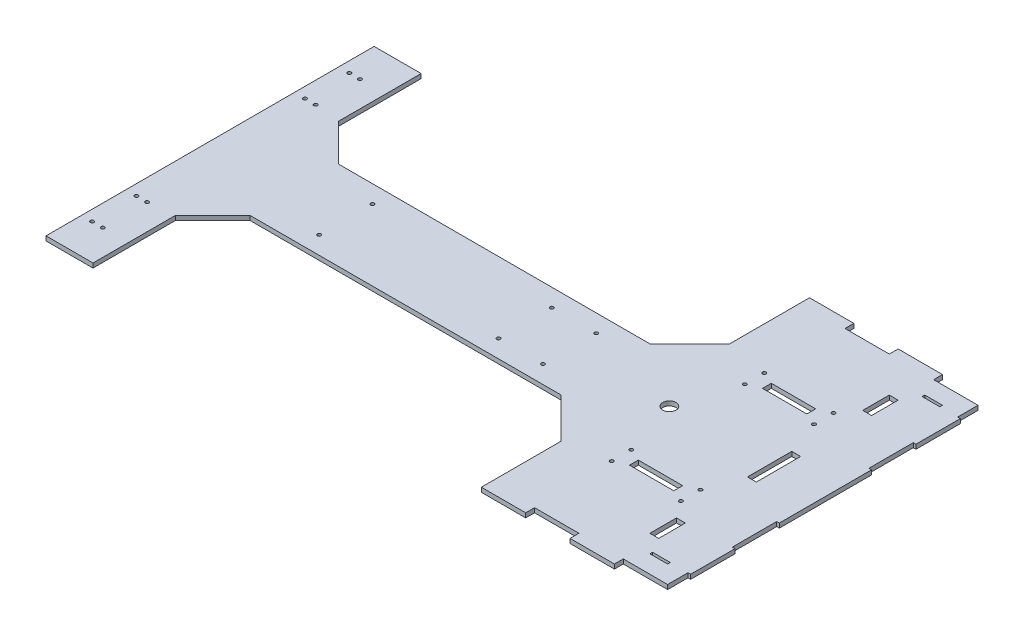
SolidWorks part; units mm, degrees
material "아크릴(내충격성)"
ref_plane "정면" through (0, 0, 0) normal (0, 0, 1) x (1, 0, 0)
ref_plane "윗면" through (0, 0, 0) normal (0, 1, 0) x (1, 0, 0)
ref_plane "우측면" through (0, 0, 0) normal (1, 0, 0) x (0, 0, -1)
sketch "스케치1" plane through (0, 0, 0) normal (0, 1, 0) x (1, 0, 0)
  line L0 (-113.0197, -185) -> (116.1534, -185) construction
  line L1 (-50, 175) -> (0, 175)
  line L2 (-100, 175) -> (-100, -175)
  line L3 (-50, -175) -> (0, -175)
  line L4 (100, 175) -> (100, -175)
  line L5 (-100, 175) -> (100, -175) construction
  line L6 (-100, -175) -> (100, 175) construction
  line L7 (-242.4397, 0) -> (206.3887, 0) construction
  line L8 (-100, -175) -> (-100, -185)
  line L9 (-100, -185) -> (-50, -185)
  line L10 (-50, -185) -> (-50, -175)
  line L11 (0, -175) -> (0, -185)
  line L12 (0, -185) -> (50, -185)
  line L13 (50, -185) -> (50, -175)
  line L14 (50, 185) -> (50, 175)
  line L15 (0, 185) -> (50, 185)
  line L16 (0, 175) -> (0, 185)
  line L17 (-50, 185) -> (-50, 175)
  line L18 (-100, 185) -> (-50, 185)
  line L19 (-100, 175) -> (-100, 185)
  line L20 (50, 175) -> (100, 175)
  line L21 (50, -175) -> (100, -175)
  point P0 (0, 0)
  dimension "D1" = 350
  dimension "D2" = 200
  dimension "D3" = 10
  dimension "D4" = 50
  dimension "D5" = 50
  dimension "D6" = 50
extrude "보스-돌출1" add sketch "스케치1" along normal blind 5
sketch "스케치2" plane through (0, 5, 0) normal (0, 1, 0) x (1, 0, 0)
  line L0 (0, 155) -> (0, -155) construction
  line L1 (0, -155) -> (100, -155) construction
  line L2 (100, -175) -> (100, 175) construction
  line L3 (0, 155) -> (100, 155) construction
  line L4 (100, 175) -> (50, 175) construction
  line L5 (50, -175) -> (100, -175) construction
  line L18 (124.0343, 0) -> (-128.3419, 0) construction
  line L23 (80, 155) -> (60, 155)
  line L24 (80, 155) -> (80, 152)
  line L25 (80, 152) -> (60, 152)
  line L26 (60, 155) -> (60, 152)
  line L31 (80, -152) -> (60, -152)
  line L32 (60, -155) -> (60, -152)
  line L33 (80, -155) -> (60, -155)
  line L34 (80, -155) -> (80, -152)
  line L39 (40, 155) -> (40, -155) construction
  line L40 (40, 105) -> (50, 105)
  line L41 (40, 135) -> (50, 135)
  line L42 (40, 135) -> (40, 105)
  line L43 (40, -135) -> (50, -135)
  line L44 (50, 135) -> (50, 105)
  line L45 (40, -105) -> (50, -105)
  line L46 (40, 25) -> (50, 25)
  line L47 (40, -25) -> (50, -25)
  line L48 (50, 25) -> (50, -25)
  line L49 (40, 25) -> (40, -25)
  line L50 (40, -105) -> (40, -135)
  line L51 (50, -105) -> (50, -135)
  dimension "D1" = 20
  dimension "D2" = 20
  dimension "D3" = 20
  dimension "D4" = 20
  dimension "D6" = 10
  dimension "D7" = 20
  dimension "D8" = 3
  dimension "D9" = 20
  dimension "D10" = 30
  dimension "D11" = 25
  dimension "D12" = 50
  dimension "D13" = 20
  dimension "D5" = 60
  dimension "D14" = 30
extrude "컷-돌출1" cut sketch "스케치2" against normal through all
sketch "스케치3" plane through (0, 5, 0) normal (0, 1, 0) x (1, 0, 0)
  line L0 (0, 0) -> (-919.3874, 0) construction
  line L1 (-100, 185) -> (-100, -185) construction
  line L2 (-540.91, 50) -> (-225, 50)
  line L4 (-540.91, -50) -> (-225, -50)
  line L6 (-540.91, 50) -> (-100, -50) construction
  line L7 (-540.91, -50) -> (-100, 50) construction
  line L8 (-540.91, 50) -> (-540.91, 185)
  line L9 (-590.91, -185) -> (-540.91, -185)
  line L10 (-590.91, -185) -> (-590.91, 185)
  line L11 (-590.91, 185) -> (-540.91, 185)
  line L12 (-540.91, -185) -> (-540.91, -50)
  line L13 (-590.91, -185) -> (-540.91, 185) construction
  line L14 (-590.91, 185) -> (-540.91, -185) construction
  line L15 (-50, 175) -> (-100, 175) construction
  line L16 (-50, -175) -> (-100, -175) construction
  line L19 (-100, 50) -> (-100, -50)
  line L20 (-225, 50) -> (-100, 50)
  line L21 (-225, -50) -> (-100, -50)
  point P3 (-320.455, 0)
  point P10 (-565.91, 0)
  dimension "D1" = 370
  dimension "D2" = 50
  dimension "D3" = 440.91
  dimension "D4" = 100
extrude "보스-돌출2" add sketch "스케치3" against normal blind 5
sketch "스케치4" plane through (0, 5, 0) normal (0, 1, 0) x (1, 0, 0)
  line L0 (-590.91, 185) -> (-590.91, -185) construction
  line L1 (-540.91, 185) -> (-590.91, 185) construction
  line L2 (-590.91, -185) -> (-540.91, -185) construction
  circle A0 centre (-578.91, 145) radius 2
  circle A1 centre (-578.91, 95) radius 2
  circle A2 centre (-566.91, 145) radius 2
  circle A3 centre (-566.91, 95) radius 2
  circle A4 centre (-578.91, -145) radius 2
  circle A5 centre (-578.91, -95) radius 2
  circle A6 centre (-566.91, -95) radius 2
  circle A7 centre (-566.91, -145) radius 2
  dimension "12" = 12
  dimension "D2" = 12
  dimension "D3" = 12
  dimension "D4" = 12
  dimension "D5" = 50
  dimension "D6" = 40
  dimension "D7" = 12
  dimension "D8" = 12
  dimension "D9" = 12
  dimension "D10" = 12
  dimension "D11" = 50
  dimension "D12" = 40
extrude "컷-돌출2" cut sketch "스케치4" against normal through all
sketch "스케치6" plane through (0, 5, 0) normal (0, 1, 0) x (1, 0, 0)
  line L0 (80, 152) -> (100, 152) construction
  line L1 (100, -175) -> (100, 175) construction
  line L2 (80, -152) -> (100, -152) construction
  line L3 (100, -102) -> (103, -102)
  line L4 (100, 152) -> (103, 152)
  line L5 (100, 152) -> (100, 102)
  line L6 (100, -152) -> (103, -152)
  line L7 (103, 152) -> (103, 102)
  line L8 (100, -52) -> (103, -52)
  line L9 (103, -102) -> (103, -152)
  line L10 (100, 52) -> (103, 52)
  line L11 (100, 102) -> (103, 102)
  line L12 (100, -102) -> (100, -152)
  line L13 (103, 52) -> (103, -52)
  line L14 (100, 52) -> (100, -52)
  dimension "D1" = 3
  dimension "D2" = 50
  dimension "D3" = 50
  dimension "D5" = 50
extrude "보스-돌출3" add sketch "스케치6" against normal blind 5
sketch "스케치7" plane through (0, 5, 0) normal (0, 1, 0) x (1, 0, 0)
  line L0 (-540.91, -185) -> (-537.91, -185)
  line L1 (-566.91, 95) -> (-100, 95) construction
  line L2 (-100, 185) -> (-100, 50) construction
  line L3 (-566.91, -95) -> (-100, -95) construction
  line L4 (-100, -50) -> (-100, -185) construction
  line L5 (-537.91, 92) -> (-495.91, 50)
  line L7 (-100, 50) -> (-540.91, 50) construction
  line L8 (-537.91, -92) -> (-495.91, -50)
  line L9 (-540.91, -50) -> (-100, -50) construction
  line L10 (-100, 95) -> (-145, 50)
  line L11 (-100, -95) -> (-145, -50)
  line L13 (-540.91, 50) -> (-495.91, 50)
  line L14 (-495.91, -50) -> (-540.91, -50)
  line L16 (-145, 50) -> (-100, 50)
  line L17 (-100, 50) -> (-100, 95)
  line L18 (-145, -50) -> (-100, -50)
  line L19 (-100, -50) -> (-100, -95)
  line L20 (-537.91, -185) -> (-537.91, -92)
  line L21 (-540.91, 185) -> (-537.91, 185)
  line L22 (-537.91, 92) -> (-537.91, 185)
  line L26 (-540.91, 185) -> (-540.91, 50)
  line L27 (-540.91, -50) -> (-540.91, -185)
  dimension "D1" = 3
extrude "보스-돌출4" add sketch "스케치7" against normal blind 5
sketch "스케치8" plane through (0, 5, 0) normal (0, 1, 0) x (1, 0, 0)
  line L0 (103, 0) -> (-190.2482, 0) construction
  line L1 (103, -52) -> (103, 52) construction
  line L2 (-58, 80) -> (32, 80) construction
  line L3 (40, 135) -> (40, 105) construction
  line L4 (-52, 90.1952) -> (-52, 60.3071) construction
  line L5 (-38, 80) -> (12, 80)
  line L6 (-38, 80) -> (-38, 70)
  line L7 (-38, 70) -> (12, 70)
  line L8 (12, 80) -> (12, 70)
  line L9 (-58, 70) -> (32, 70) construction
  line L10 (26, 89.397) -> (26, 62.9791) construction
  line L11 (-63, 86) -> (27, 86) construction
  line L12 (-58, 64) -> (32, 64) construction
  line L13 (12, -80) -> (12, -70)
  line L14 (-38, -80) -> (12, -80)
  line L15 (-38, -70) -> (12, -70)
  line L16 (-38, -80) -> (-38, -70)
  circle A0 centre (-52, 86) radius 2
  circle A1 centre (-52, 64) radius 2
  circle A2 centre (26, 86) radius 2
  circle A3 centre (26, 64) radius 2
  circle A4 centre (-52, -86) radius 2
  circle A5 centre (-52, -64) radius 2
  circle A6 centre (26, -64) radius 2
  circle A7 centre (26, -86) radius 2
  dimension "D1" = 80
  dimension "D2" = 90
  dimension "D3" = 8
  dimension "D4" = 20
  dimension "D5" = 20
  dimension "D6" = 10
  dimension "D7" = 6
  dimension "D8" = 6
  dimension "D9" = 6
  dimension "D10" = 6
extrude "컷-돌출3" cut sketch "스케치8" against normal through all
sketch "스케치9" plane through (0, 5, 0) normal (0, 1, 0) x (1, 0, 0)
  line L0 (-590.91, 0) -> (-107.718, 0) construction
  line L1 (-590.91, 185) -> (-590.91, -185) construction
  line L2 (-537.91, 92) -> (-537.91, -92) construction
  line L3 (-537.91, 30) -> (-107.718, 30) construction
  line L4 (-437.91, 60.414) -> (-437.91, 0) construction
  line L5 (-235.58, 0) -> (-235.58, 62.7869) construction
  line L6 (-185.58, 0) -> (-185.58, 62.7869) construction
  circle A0 centre (-437.91, 30) radius 2
  circle A1 centre (-235.58, 30) radius 2
  circle A2 centre (-185.58, 30) radius 2
  circle A3 centre (-185.58, -30) radius 2
  circle A4 centre (-235.58, -30) radius 2
  circle A5 centre (-437.91, -30) radius 2
  dimension "D1" = 30
  dimension "D2" = 100
  dimension "D3" = 50
  dimension "D4" = 202.33
extrude "컷-돌출4" cut sketch "스케치9" against normal through all
sketch "스케치10" plane through (0, 5, 0) normal (0, 1, 0) x (1, 0, 0)
  line L1 (-13, 0) -> (-73, 0)
  line L2 (-38, 70) -> (12, 70) construction
  line L3 (-38, 70) -> (12, 70)
  circle A1 centre (-73, 0) radius 7.5
  circle A2 centre (-73, 0) radius 60
  dimension "D1" = 15
  dimension "D2" = 120
extrude "컷-돌출5" cut sketch "스케치10" against normal through all
